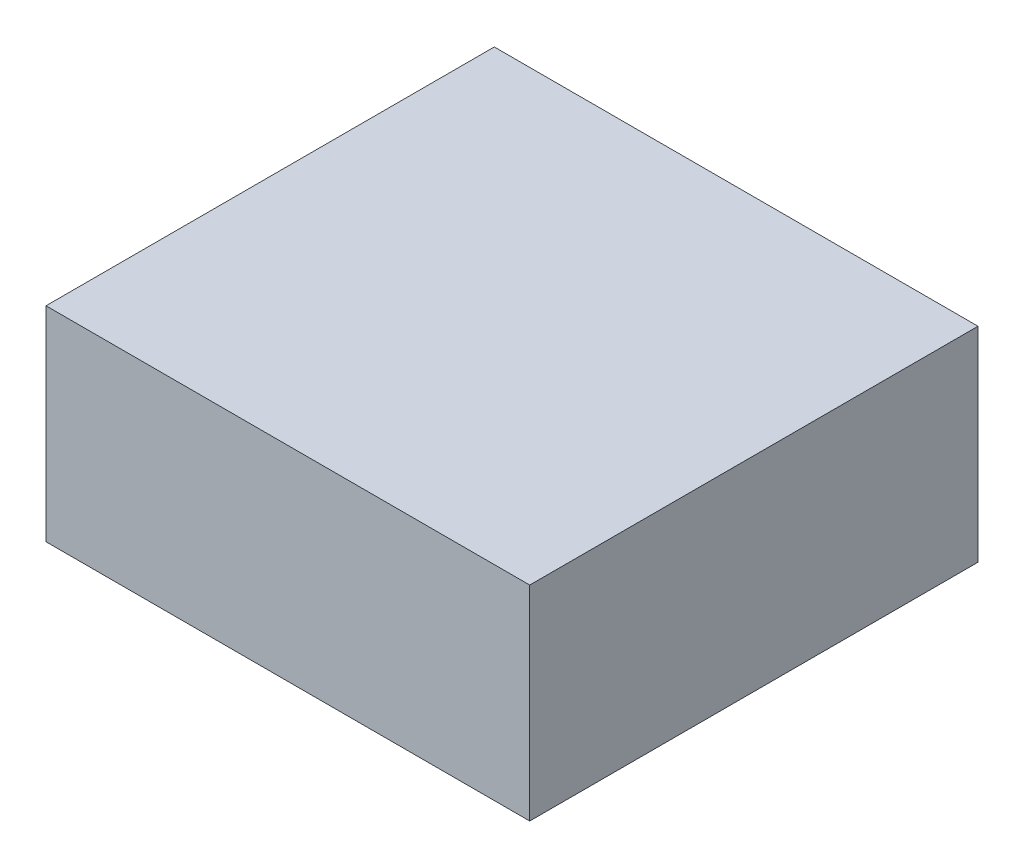
SolidWorks part; units mm, degrees
ref_plane "Front Plane" through (0, 0, 0) normal (0, 0, 1) x (1, 0, 0)
ref_plane "Top Plane" through (0, 0, 0) normal (0, 1, 0) x (1, 0, 0)
ref_plane "Right Plane" through (0, 0, 0) normal (1, 0, 0) x (0, 0, -1)
sketch "Sketch1" plane through (0, 0, 0) normal (0, 1, 0) x (1, 0, 0)
  line L1 (0, 0) -> (-180.34, 0)
  line L2 (0, 0) -> (0, 167.132)
  line L3 (0, 167.132) -> (-180.34, 167.132)
  line L4 (-180.34, 0) -> (-180.34, 167.132)
  dimension "D1" = 180.34
  dimension "D2" = 167.132
extrude "Boss-Extrude1" add sketch "Sketch1" along normal blind 76.2
